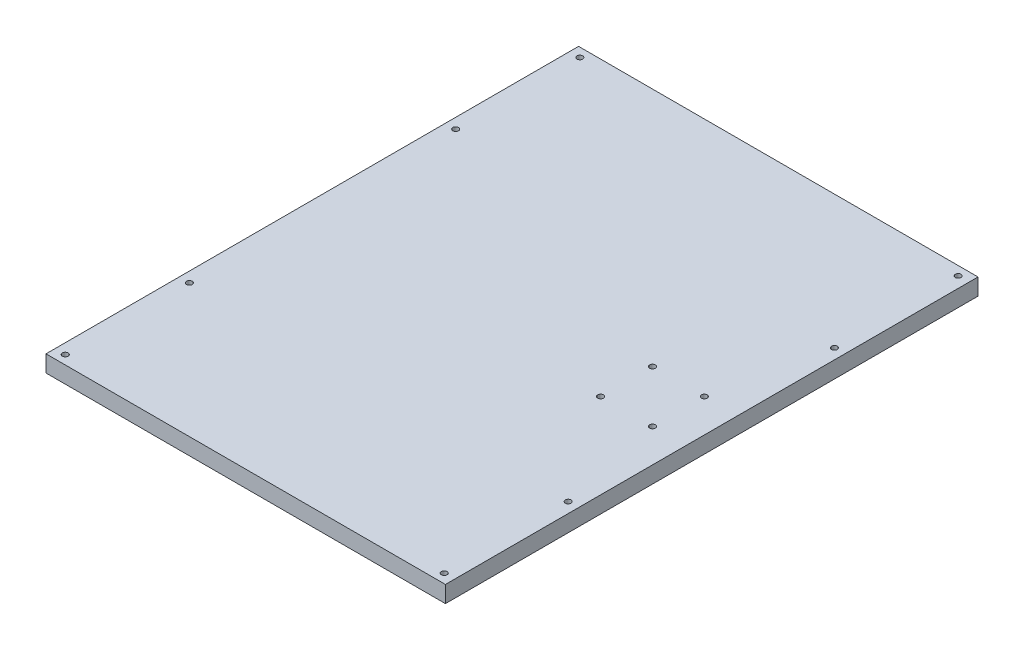
SolidWorks part; units mm, degrees
material "6061-T6 (SS)"
ref_plane "Front Plane" through (0, 0, 0) normal (0, 0, 1) x (1, 0, 0)
ref_plane "Top Plane" through (0, 0, 0) normal (0, 1, 0) x (1, 0, 0)
ref_plane "Right Plane" through (0, 0, 0) normal (1, 0, 0) x (0, 0, -1)
sketch "Sketch1" plane through (0, 0, 0) normal (0, 1, 0) x (1, 0, 0)
  line L2 (0.0247, -55.1067) -> (152.4247, -55.1067)
  line L4 (152.4247, 148.0933) -> (0.0247, 148.0933)
  line L13 (152.4247, -55.1067) -> (152.4247, 148.0933)
  line L15 (0.0247, -55.1067) -> (0.0247, 148.0933)
  line L16 (368.8263, 46.8075) -> (368.8263, 46.6409)
  circle A0 centre (3.9362, 144.6586) radius 1.1
  circle A1 centre (3.9362, -51.6721) radius 1.1
  circle A2 centre (148.4638, -51.6013) radius 1.1
  circle A3 centre (148.2918, 144.6586) radius 1.1
  circle A4 centre (148.4638, 97.2933) radius 1.1
  circle A5 centre (148.4638, -4.3067) radius 1.1
  circle A6 centre (3.9362, -4.3067) radius 1.1
  circle A7 centre (3.9362, 97.2933) radius 1.1
  dimension "D1" = 152.4
  dimension "D4" = 2.2
  dimension "D6" = 2.2
  dimension "D7" = 3.9609
  dimension "D11" = 2.2
  dimension "D13" = 50.8
  dimension "D14" = 3.9609
  dimension "D15" = 2.2
  dimension "D16" = 50.8
  dimension "D17" = 4.1329
  dimension "D18" = 3.4347
  dimension "D19" = 2.2
  dimension "D20" = 2.2
  dimension "D21" = 3.9115
  dimension "D22" = 50.8
  dimension "D23" = 3.4347
  dimension "D26" = 50.8
  dimension "D27" = 3.4347
  dimension "D28" = 3.9115
  dimension "D29" = 2.2
  dimension "D36" = 50.8
  dimension "D2" = 203.2
  dimension "D3" = 152.4
  dimension "D5" = 144.5276
  dimension "D8" = 3.5054
  dimension "D9" = 148.0933
  dimension "D10" = 152.4247
  dimension "D12" = 3.9609
  dimension "D24" = 3.9115
extrude "Boss-Extrude1" add sketch "Sketch1" along normal blind 6.35 contours L15 L2 L13 L4 A7 A6 A5 A4 A3 A2 A1 A0
sketch "Sketch2" plane through (0, 6.35, 0) normal (0, 1, 0) x (1, 0, 0)
  line L0 (152.4247, 148.0933) -> (152.4247, -55.1067)
  circle A1 centre (119.9247, 56.3933) radius 1.1
  circle A2 centre (119.9247, 36.5933) radius 1.1
  circle A3 centre (139.7247, 56.3933) radius 1.1
  circle A4 centre (139.7247, 36.5933) radius 1.1
  circle A5 centre (3.9362, 97.2933) radius 1.1 construction
  dimension "D1" = 2.2
  dimension "D2" = 115.9885
  dimension "D3" = 135.7885
  dimension "D4" = 40.9
  dimension "D5" = 60.7
extrude "Cut-Extrude1" cut sketch "Sketch2" against normal blind 6.35 contours A1 | A2 | A4 | A3
